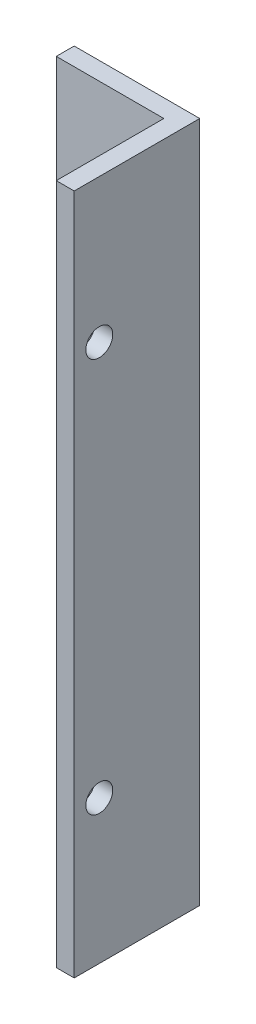
SolidWorks part; units mm, degrees
ref_plane "前视基准面" through (0, 0, 0) normal (0, 0, 1) x (1, 0, 0)
ref_plane "上视基准面" through (0, 0, 0) normal (0, 1, 0) x (1, 0, 0)
ref_plane "右视基准面" through (0, 0, 0) normal (1, 0, 0) x (0, 0, -1)
sketch "草图2" plane through (0, 0, 0) normal (0, 1, 0) x (1, 0, 0)
  line L0 (0, 0) -> (0, 14)
  line L1 (0, 14) -> (-14, 14)
  line L2 (-14, 14) -> (-14, 12)
  line L3 (-14, 12) -> (-2, 12)
  line L4 (-2, 12) -> (-2, 0)
  line L5 (-2, 0) -> (0, 0)
extrude "凸台-拉伸1" add sketch "草图2" along normal blind 76
sketch "草图3" plane through (0, 0, 0) normal (1, 0, 0) x (0, 0, -1)
  line L0 (0, 76) -> (0, 0) construction
  line L1 (0, 76) -> (14, 76) construction
  line L2 (0, 0) -> (14, 0) construction
  circle A0 centre (2.8, 60) radius 1.5
  circle A1 centre (2.8, 16) radius 1.5
  point P10 (0.7442, 11.3134)
  dimension "D1" = 3
  dimension "D2" = 3
  dimension "D3" = 2.8
  dimension "D4" = 16
  dimension "D5" = 2.8
  dimension "D6" = 16
extrude "切除-拉伸1" cut sketch "草图3" against normal blind 76
sketch "草图4" plane through (0, 0, -14) normal (0, 0, -1) x (-1, 0, 0)
  line L0 (0, 76) -> (0, 0) construction
  circle A0 centre (7, 23) radius 2.5
  circle A1 centre (7, 53) radius 2.5
  point P6 (0, 38)
  dimension "D1" = 5
  dimension "D2" = 5
  dimension "D3" = 7
  dimension "D4" = 7
  dimension "D5" = 30
  dimension "D6" = 15
extrude "切除-拉伸2" cut sketch "草图4" against normal blind 76
